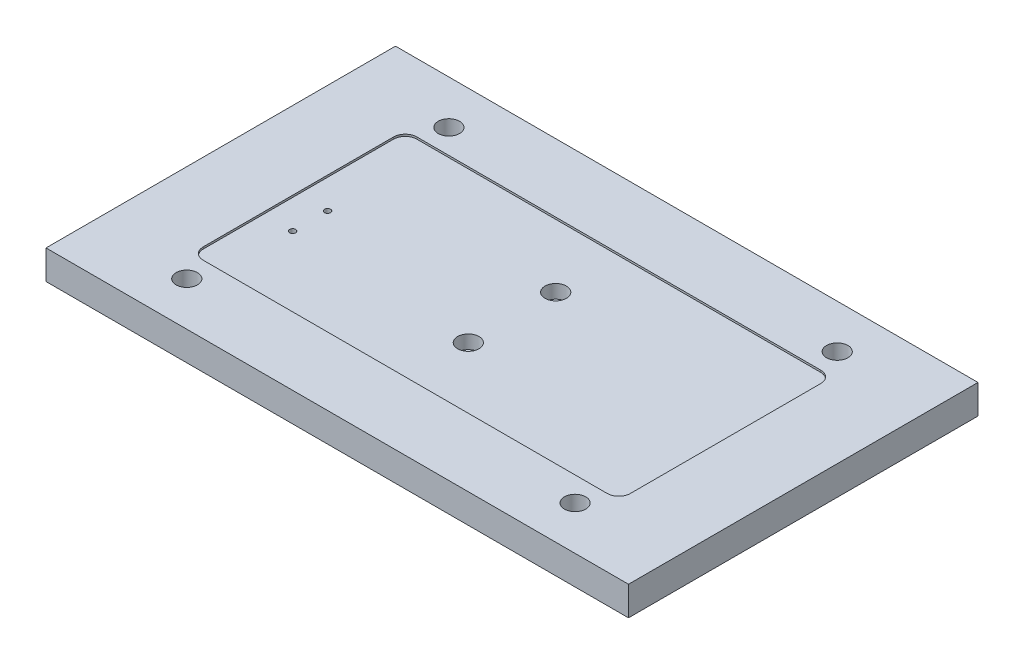
SolidWorks part; units mm, degrees
ref_plane "Спереди" through (0, 0, 0) normal (0, 0, 1) x (1, 0, 0)
ref_plane "Сверху" through (0, 0, 0) normal (0, 1, 0) x (1, 0, 0)
ref_plane "Справа" through (0, 0, 0) normal (1, 0, 0) x (0, 0, -1)
other "Configuration Table"
sketch "Эскиз1" plane through (0, 0, 0) normal (0, 1, 0) x (1, 0, 0)
  line L1 (-150, -90) -> (150, -90)
  line L2 (-150, -90) -> (-150, 90)
  line L3 (-150, 90) -> (150, 90)
  line L4 (150, -90) -> (150, 90)
  line L5 (-150, -90) -> (150, 90) construction
  line L6 (-150, 90) -> (150, -90) construction
  point P0 (0, 0)
  dimension "D1" = 300
  dimension "D2" = 180
extrude "Бобышка-Вытянуть1" add sketch "Эскиз1" along normal blind 15
sketch "Эскиз2" plane through (0, 15, 0) normal (0, 1, 0) x (1, 0, 0)
  circle A0 centre (100, -67.5) radius 2.5 construction
  circle A1 centre (100, 67.5) radius 2.5 construction
  circle A2 centre (0, 22.5) radius 2.5 construction
  circle A3 centre (0, -22.5) radius 2.5 construction
  circle A4 centre (-100, -67.5) radius 2.5 construction
  circle A5 centre (-100, 67.5) radius 2.5 construction
  circle A6 centre (100, -67.5) radius 2.5
  circle A7 centre (100, 67.5) radius 2.5
  circle A8 centre (0, 22.5) radius 2.5
  circle A9 centre (0, -22.5) radius 2.5
  circle A10 centre (-100, -67.5) radius 2.5
  circle A11 centre (-100, 67.5) radius 2.5
  circle A12 centre (100, -67.5) radius 3
  circle A13 centre (100, 67.5) radius 3
  circle A14 centre (0, 22.5) radius 3
  circle A15 centre (0, -22.5) radius 3
  circle A16 centre (-100, -67.5) radius 3
  circle A17 centre (-100, 67.5) radius 3
  dimension "D1" = 0.5
extrude "Вырез-Вытянуть1" cut sketch "Эскиз2" against normal through all contours A9 | A15 A9 | A10 | A16 A10 | A6 | A12 A6 | A13 A7 | A7 | A14 A8 | A8 | A11 | A17 A11
sketch "Эскиз3" plane through (0, 15, 0) normal (0, 1, 0) x (1, 0, 0)
  circle A0 centre (-100, -67.5) radius 5 construction
  circle A1 centre (100, -67.5) radius 5 construction
  circle A2 centre (100, 67.5) radius 5 construction
  circle A3 centre (0, -22.5) radius 5 construction
  circle A4 centre (0, 22.5) radius 5 construction
  circle A5 centre (-100, 67.5) radius 5 construction
  circle A6 centre (-100, -67.5) radius 5
  circle A7 centre (100, -67.5) radius 5
  circle A8 centre (100, 67.5) radius 5
  circle A9 centre (0, -22.5) radius 5
  circle A10 centre (0, 22.5) radius 5
  circle A11 centre (-100, 67.5) radius 5
  circle A12 centre (100, -67.5) radius 5.5
  circle A13 centre (100, 67.5) radius 5.5
  circle A14 centre (0, -22.5) radius 5.5
  circle A15 centre (0, 22.5) radius 5.5
  circle A16 centre (-100, 67.5) radius 5.5
  circle A17 centre (-100, -67.5) radius 5.5
  circle M1 centre (-100, -67.5) radius 3
  circle M2 centre (100, -67.5) radius 3
  circle M3 centre (100, 67.5) radius 3
  circle M4 centre (0, 22.5) radius 3
  circle M5 centre (-100, 67.5) radius 3
  circle M6 centre (0, -22.5) radius 3
  dimension "D1" = 0.5
extrude "Вырез-Вытянуть3" cut sketch "Эскиз3" against normal blind 8 contours A9 M6 | A14 A9 | A6 M1 | A17 A6 | A7 M2 | A12 A7 | A10 M4 | A15 A10 | A11 M5 | A16 A11 | A13 A8 | A8 M3
sketch "Эскиз4" plane through (0, 15, 0) normal (0, 1, 0) x (1, 0, 0)
  line L0 (-1000, 0) -> (49000, 0) construction
  line L1 (-110, -49) -> (-110, 49)
  line L2 (-104, -55) -> (104, -55)
  line L3 (-104, 55) -> (104, 55)
  line L4 (110, -49) -> (110, 49)
  line L5 (-110, -55) -> (110, 55) construction
  line L6 (-110, 55) -> (110, -55) construction
  arc A0 (110, -49) -> (104, -55) centre (104, -49) cw
  arc A1 (-110, -49) -> (-104, -55) centre (-104, -49) ccw
  arc A2 (110, 49) -> (104, 55) centre (104, 49) ccw
  arc A3 (-104, 55) -> (-110, 49) centre (-104, 49) ccw
  point P4 (0, 0)
  dimension "D4" = 6
  dimension "D5" = 6
  dimension "D6" = 6
  dimension "D7" = 6
  dimension "D1" = 110
  dimension "D2" = 220
extrude "Вырез-Вытянуть4" cut sketch "Эскиз4" against normal blind 1
sketch "Эскиз6" plane through (0, 14, 0) normal (0, 1, 0) x (1, 0, 0)
  line L4 (110, -49) -> (110, 49)
  line L5 (104, 55) -> (-104, 55)
  line L6 (-110, 49) -> (-110, -49)
  line L7 (-104, -55) -> (104, -55)
  line L8 (110, -49) -> (110, 49)
  line L9 (104, 55) -> (-104, 55)
  line L10 (-110, 49) -> (-110, -49)
  line L11 (-104, -55) -> (104, -55)
  circle A0 centre (-95, -18) radius 1.5875 construction
  circle A1 centre (-95, -18) radius 1.5875 construction
  circle A2 centre (-95, 0) radius 1.5875 construction
  circle A3 centre (-95, 0) radius 1.5875 construction
  arc A4 (104, -55) -> (110, -49) centre (104, -49) ccw
  arc A5 (110, 49) -> (104, 55) centre (104, 49) ccw
  arc A6 (-104, 55) -> (-110, 49) centre (-104, 49) ccw
  arc A7 (-110, -49) -> (-104, -55) centre (-104, -49) ccw
  arc A8 (104, -55) -> (110, -49) centre (104, -49) ccw
  arc A9 (110, 49) -> (104, 55) centre (104, 49) ccw
  arc A10 (-104, 55) -> (-110, 49) centre (-104, 49) ccw
  arc A11 (-110, -49) -> (-104, -55) centre (-104, -49) ccw
  circle A12 centre (-95, 0) radius 1.55
  circle A13 centre (-95, -18) radius 1.55
  dimension "D2" = 3.1
  dimension "D1" = 0
extrude "Вырез-Вытянуть6" cut sketch "Эскиз6" against normal up to surface (9 mm away) contours A13 | A12
